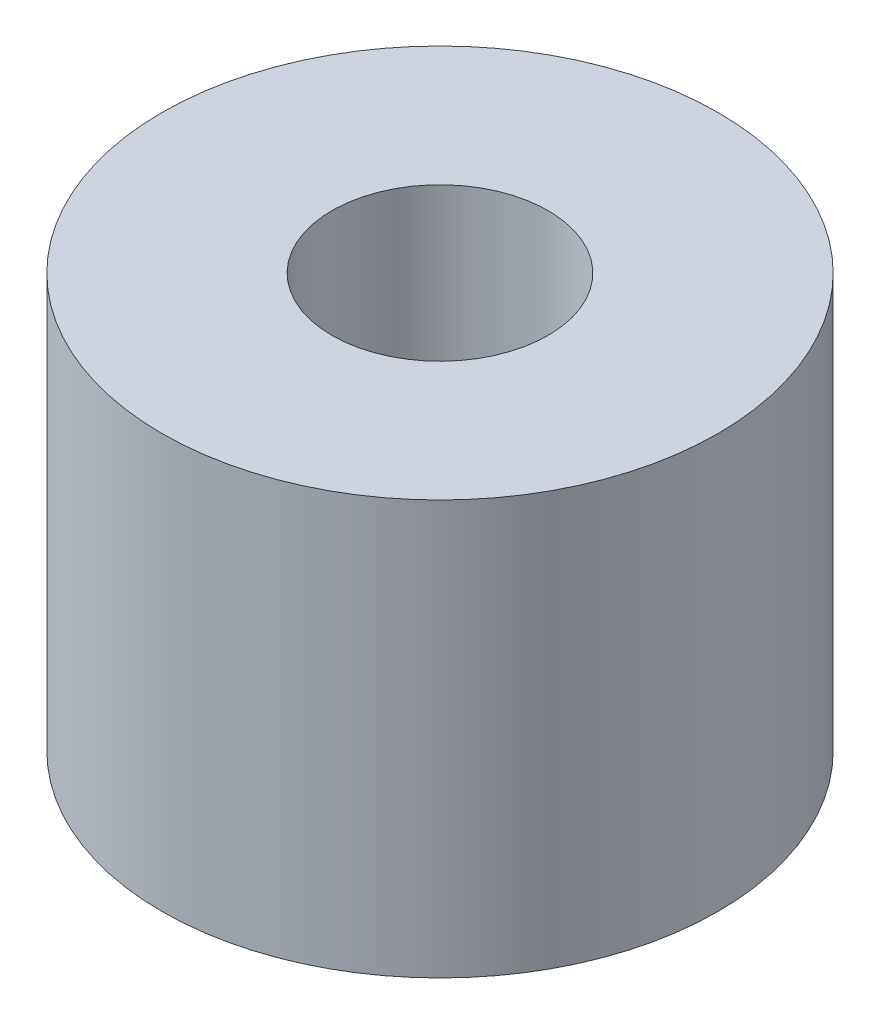
SolidWorks part; units mm, degrees
ref_plane "前视基准面" through (0, 0, 0) normal (0, 0, 1) x (1, 0, 0)
ref_plane "上视基准面" through (0, 0, 0) normal (0, 1, 0) x (1, 0, 0)
ref_plane "右视基准面" through (0, 0, 0) normal (1, 0, 0) x (0, 0, -1)
other "Configuration Table"
sketch "草图2" plane through (0, 0, 0) normal (0, 1, 0) x (1, 0, 0)
  circle A18 centre (0, 0) radius 4.5
  circle A19 centre (0, 0) radius 1.75
  dimension "D1" = 3.5
  dimension "D2" = 9
extrude "凸台-拉伸1" add sketch "草图2" along normal blind 6.7
